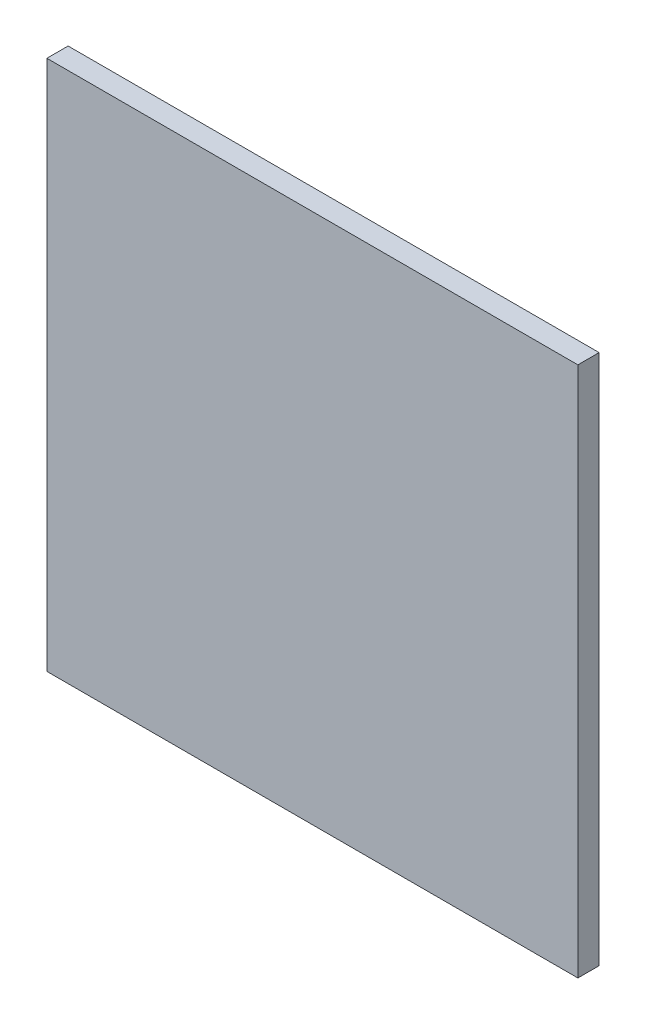
SolidWorks part; units mm, degrees
ref_plane "Front Plane" through (0, 0, 0) normal (0, 0, 1) x (1, 0, 0)
ref_plane "Top Plane" through (0, 0, 0) normal (0, 1, 0) x (1, 0, 0)
ref_plane "Right Plane" through (0, 0, 0) normal (1, 0, 0) x (0, 0, -1)
sketch "Sketch1" plane through (0, 0, 0) normal (0, 0, 1) x (1, 0, 0)
  line L1 (0, 0) -> (25.4, 0)
  line L2 (0, 0) -> (0, 25.4)
  line L3 (0, 25.4) -> (25.4, 25.4)
  line L4 (25.4, 0) -> (25.4, 25.4)
  dimension "D1" = 25.4
  dimension "D2" = 25.4
extrude "Boss-Extrude1" add sketch "Sketch1" along normal blind 1.016
